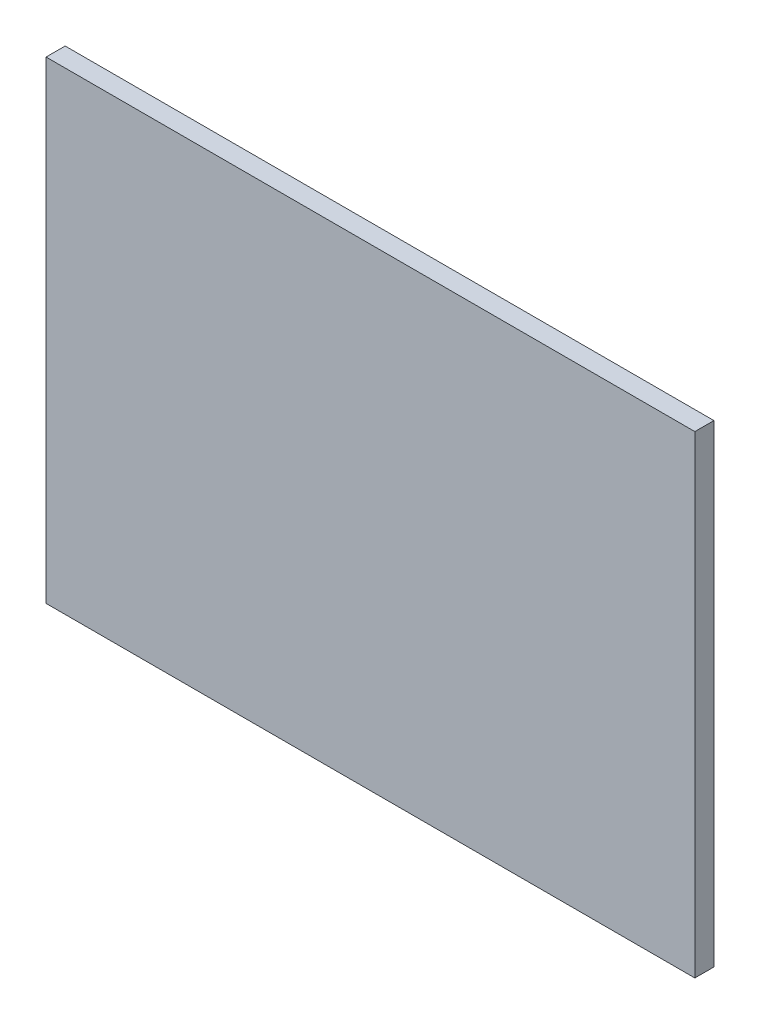
SolidWorks part; units mm, degrees
ref_plane "Plan de face" through (0, 0, 0) normal (0, 0, 1) x (1, 0, 0)
ref_plane "Plan de dessus" through (0, 0, 0) normal (0, 1, 0) x (1, 0, 0)
ref_plane "Plan de droite" through (0, 0, 0) normal (1, 0, 0) x (0, 0, -1)
sketch "Esquisse1" plane through (0, 0, 0) normal (0, 0, 1) x (1, 0, 0)
  line L1 (0, 0) -> (170, 0)
  line L2 (0, 0) -> (0, 124)
  line L3 (0, 124) -> (170, 124)
  line L4 (170, 0) -> (170, 124)
  dimension "D1" = 170
  dimension "D2" = 124
extrude "Boss.-Extru.1" add sketch "Esquisse1" along normal blind 5
